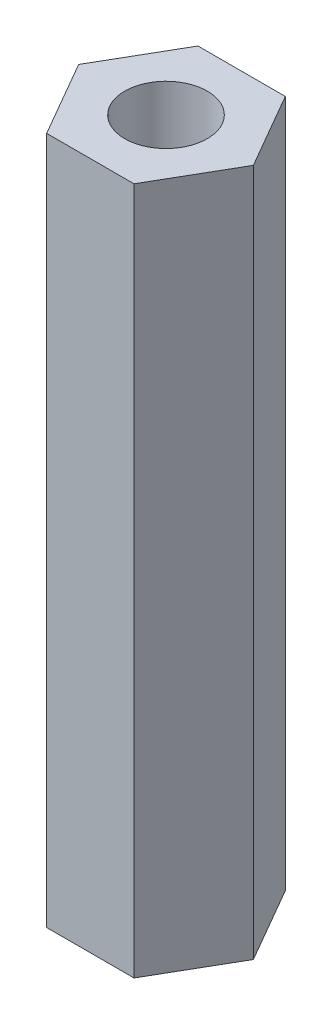
SolidWorks part; units mm, degrees
ref_plane "前视基准面" through (0, 0, 0) normal (0, 0, 1) x (1, 0, 0)
ref_plane "上视基准面" through (0, 0, 0) normal (0, 1, 0) x (1, 0, 0)
ref_plane "右视基准面" through (0, 0, 0) normal (1, 0, 0) x (0, 0, -1)
sketch "草图1" plane through (0, 0, 0) normal (0, 1, 0) x (1, 0, 0)
  line L1 (-4.1472, 7.5722) -> (-5.7349, 10.3222)
  line L2 (-5.7349, 10.3222) -> (-8.9103, 10.3222)
  line L3 (-8.9103, 10.3222) -> (-10.498, 7.5722)
  line L4 (-10.498, 7.5722) -> (-8.9103, 4.8222)
  line L5 (-8.9103, 4.8222) -> (-5.7349, 4.8222)
  line L6 (-5.7349, 4.8222) -> (-4.1472, 7.5722)
  circle A0 centre (-7.3226, 7.5722) radius 1.5
  circle A1 centre (-7.3226, 7.5722) radius 2.75 construction
extrude "凸台-拉伸1" add sketch "草图1" along normal blind 25
